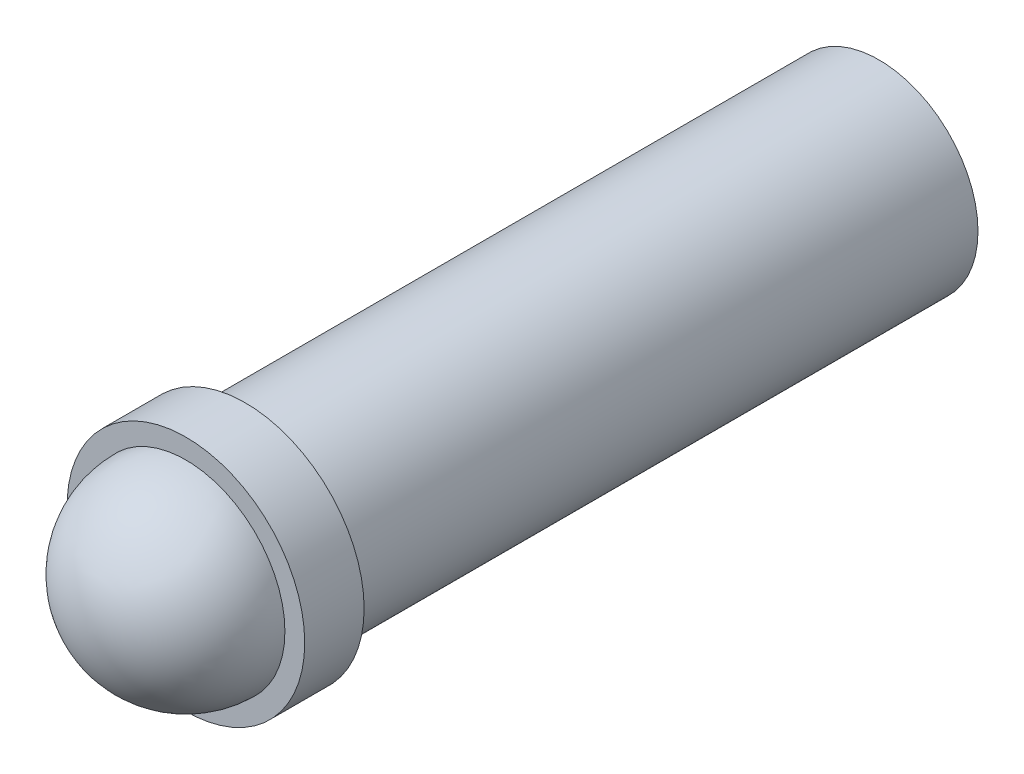
SolidWorks part; units mm, degrees
ref_plane "Front Plane" through (0, 0, 0) normal (0, 0, 1) x (1, 0, 0)
ref_plane "Top Plane" through (0, 0, 0) normal (0, 1, 0) x (1, 0, 0)
ref_plane "Right Plane" through (0, 0, 0) normal (1, 0, 0) x (0, 0, -1)
sketch "Sketch1" plane through (0, 0, 0) normal (0, 0, 1) x (1, 0, 0)
  circle A0 centre (0, 0) radius 10
  dimension "D1" = 20
extrude "Boss-Extrude1" add sketch "Sketch1" along normal blind 80
fillet "Fillet1" radius 10 1 edges at (10, 0, 80)
sketch "Sketch2" plane through (0, 0, 0) normal (0, 0, 1) x (1, 0, 0)
  circle A0 centre (0, 0) radius 10 construction
  circle A1 centre (0, 0) radius 10
  circle A2 centre (0, 0) radius 12
  dimension "D1" = 2
extrude "Boss-Extrude2" add sketch "Sketch2" along normal blind 6 from offset 64
